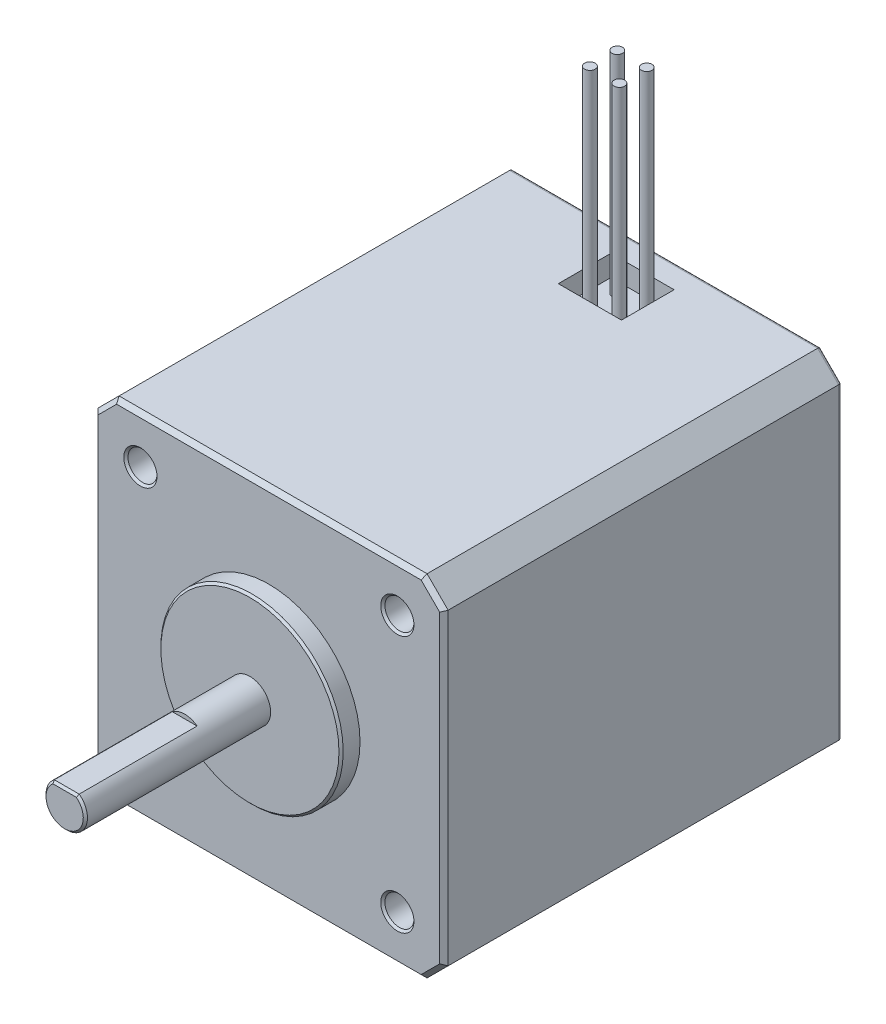
SolidWorks part; units mm, degrees
ref_plane "Plan de face" through (0, 0, 0) normal (0, 0, 1) x (1, 0, 0)
ref_plane "Plan de dessus" through (0, 0, 0) normal (0, 1, 0) x (1, 0, 0)
ref_plane "Plan de droite" through (0, 0, 0) normal (1, 0, 0) x (0, 0, -1)
ref_plane "Plan1" through (21.1211, 0, 0) normal (1, 0, 0) x (0, 0, -1)
sketch "Esquisse1" plane through (21.1211, 0, 0) normal (1, 0, 0) x (0, 0, -1)
  line L0 (0, 21.1211) -> (0, -21.1211)
  line L1 (0, -21.1211) -> (48.006, -21.1211)
  line L2 (48.006, -21.1211) -> (48.006, 21.1211)
  line L3 (48.006, 21.1211) -> (0, 21.1211)
extrude "Boss.-Extru.1" add sketch "Esquisse1" against normal blind 42.2423
sketch "Esquisse2" plane through (0, 0, 0) normal (0, 0, 1) x (1, 0, 0)
  circle A0 centre (0, 0) radius 11
extrude "Boss.-Extru.2" add sketch "Esquisse2" along normal blind 2.286
sketch "Esquisse3" plane through (0, 0, 2.286) normal (0, 0, 1) x (1, 0, 0)
  circle A0 centre (0, 0) radius 2.5
extrude "Boss.-Extru.3" add sketch "Esquisse3" along normal blind 22.352
sketch "Esquisse4" plane through (0, 0, 24.638) normal (0, 0, 1) x (1, 0, 0)
  line L0 (-1.5, 2) -> (1.5, 2)
  arc A0 (1.5, 2) -> (-1.5, 2) centre (0, 0) ccw
extrude "Enlèv. mat.-Extru.1" cut sketch "Esquisse4" against normal blind 14.478
sketch "Esquisse5" plane through (0, 21.1211, 0) normal (0, 1, 0) x (-1, 0, 0)
  line L0 (-3.81, -38.735) -> (-3.81, -45.085)
  line L1 (-3.81, -45.085) -> (3.81, -45.085)
  line L2 (3.81, -45.085) -> (3.81, -38.735)
  line L3 (3.81, -38.735) -> (-3.81, -38.735)
extrude "Enlèv. mat.-Extru.2" cut sketch "Esquisse5" against normal blind 2.54
ref_plane "Plan2" through (0, 0, -43.815) normal (0, 0, -1) x (-1, 0, 0)
sketch "Esquisse6" plane through (0, 0, -43.815) normal (0, 0, -1) x (-1, 0, 0)
  line L0 (-2.413, 18.5811) -> (-1.778, 18.5811)
  line L1 (-1.778, 18.5811) -> (-1.778, 43.9811)
  line L2 (-1.778, 43.9811) -> (-2.413, 43.9811)
  line L3 (-2.413, 43.9811) -> (-2.413, 18.5811)
  line L4 (-1.778, 18.5811) -> (-1.778, 43.9811) construction
revolve "Révolution1" add sketch "Esquisse6" angle 360 about L4
ref_plane "Plan3" through (0, 0, -40.513) normal (0, 0, -1) x (-1, 0, 0)
sketch "Esquisse7" plane through (0, 0, -40.513) normal (0, 0, -1) x (-1, 0, 0)
  line L0 (-2.413, 18.5811) -> (-1.778, 18.5811)
  line L1 (-1.778, 18.5811) -> (-1.778, 43.9811)
  line L2 (-1.778, 43.9811) -> (-2.413, 43.9811)
  line L3 (-2.413, 43.9811) -> (-2.413, 18.5811)
  line L4 (-1.778, 18.5811) -> (-1.778, 43.9811) construction
revolve "Révolution2" add sketch "Esquisse7" angle 360 about L4
sketch "Esquisse8" plane through (0, 0, -43.815) normal (0, 0, -1) x (-1, 0, 0)
  line L0 (1.143, 18.5811) -> (1.778, 18.5811)
  line L1 (1.778, 18.5811) -> (1.778, 43.9811)
  line L2 (1.778, 43.9811) -> (1.143, 43.9811)
  line L3 (1.143, 43.9811) -> (1.143, 18.5811)
  line L4 (1.778, 18.5811) -> (1.778, 43.9811) construction
revolve "Révolution3" add sketch "Esquisse8" angle 360 about L4
sketch "Esquisse9" plane through (0, 0, -40.513) normal (0, 0, -1) x (-1, 0, 0)
  line L0 (1.143, 18.5811) -> (1.778, 18.5811)
  line L1 (1.778, 18.5811) -> (1.778, 43.9811)
  line L2 (1.778, 43.9811) -> (1.143, 43.9811)
  line L3 (1.143, 43.9811) -> (1.143, 18.5811)
  line L4 (1.778, 18.5811) -> (1.778, 43.9811) construction
revolve "Révolution4" add sketch "Esquisse9" angle 360 about L4
hole_wizard "Dégagement M81" positions "Esquisse11" profile "Esquisse10" hole size "M8" standard "Ansi Metric"
sketch "Esquisse11" plane through (0, 0, -48.006) normal (0, 0, -1) x (-1, 0, 0)
  point P0 (0, 0)
sketch "Esquisse10" plane through (0, 0, -48.006) normal (1, 0, 0) x (0, 1, 0)
  line L0 (0, 0) -> (0, 4.191)
  line L1 (0, 4.191) -> (4.5085, 4.191)
  line L2 (4.5085, 4.191) -> (4.5085, 0)
  line L5 (4.5085, 0) -> (0, 0)
  line L10 (0, 4.191) -> (-4.5085, 4.191) construction
  line L11 (0, -6.35) -> (0, 107.95) construction
  dimension "Diamètre du perçage" = 9.017
  dimension "Profondeur du perçage" = 4.191
  dimension "Angle de pointe" = 180
hole_wizard "Diamètre du perçage Ø4.0 (4)1" positions "Esquisse13" profile "Esquisse12" hole size "Ø4.0" standard "Ansi Metric"
sketch "Esquisse13" plane through (0, 0, -48.006) normal (0, 0, -1) x (-1, 0, 0)
  point P0 (15.5, 15.5)
  point P1 (-15.5, -15.5)
  point P2 (15.5, -15.5)
  point P3 (-15.5, 15.5)
sketch "Esquisse12" plane through (-15.5, 15.5, -48.006) normal (1, 0, 0) x (0, 1, 0)
  line L0 (0, 0) -> (0, 4.191)
  line L1 (0, 4.191) -> (2, 4.191)
  line L2 (2, 4.191) -> (2, 0)
  line L5 (2, 0) -> (0, 0)
  line L10 (0, 4.191) -> (-2, 4.191) construction
  line L11 (0, -6.35) -> (0, 107.95) construction
  dimension "Diamètre du perçage" = 4
  dimension "Profondeur du perçage" = 4.191
  dimension "Angle de pointe" = 180
hole_wizard "Diamètre du perçage Ø3.5 (3.5)1" positions "Esquisse15" profile "Esquisse14" hole size "Ø3.5" standard "Ansi Metric"
sketch "Esquisse15" plane through (0, 0, 0) normal (0, 0, 1) x (1, 0, 0)
  point P0 (-15.5, 15.5)
  point P1 (15.5, 15.5)
  point P2 (-15.5, -15.5)
  point P3 (15.5, -15.5)
sketch "Esquisse14" plane through (-15.5, 15.5, 0) normal (1, 0, 0) x (0, -1, 0)
  line L0 (0, 0) -> (0, 4.572)
  line L1 (0, 4.572) -> (1.75, 4.572)
  line L2 (1.75, 4.572) -> (1.75, 0)
  line L5 (1.75, 0) -> (0, 0)
  line L10 (0, 4.572) -> (-1.75, 4.572) construction
  line L11 (0, -6.35) -> (0, 107.95) construction
  dimension "Diamètre du perçage" = 3.5
  dimension "Profondeur du perçage" = 4.572
  dimension "Angle de pointe" = 180
chamfer "Chanfrein1" distance 0.254 angle 45 12 edges at (-13.75, 15.5, 0) (17.25, 15.5, 0) (-13.75, -15.5, 0) (17.25, -15.5, 0) (0, 2, 24.638) (0, -2.5, 24.638) (11, 0, 2.286) (13.5, -15.5, -48.006) (-17.5, -15.5, -48.006) (13.5, 15.5, -48.006) (-17.5, 15.5, -48.006) (-4.5085, 0, -48.006)
chamfer "Chanfrein2" distance 2.54 angle 45 4 edges at (-21.1211, 21.1211, -24.003) (-21.1211, -21.1211, -24.003) (21.1211, 21.1211, -24.003) (21.1211, -21.1211, -24.003)
chamfer "Chanfrein3" distance 0.508 angle 45 8 edges at (19.8511, 19.8511, 0) (21.1211, 0, 0) (0, 21.1211, 0) (19.8511, -19.8511, 0) (-19.8511, 19.8511, 0) (0, -21.1211, 0) (-21.1211, 0, 0) (-19.8511, -19.8511, 0)
fillet "Congé1" radius 0.381 8 edges at (-21.1211, 0, -48.006) (-19.8511, 19.8511, -48.006) (-19.8511, -19.8511, -48.006) (0, 21.1211, -48.006) (0, -21.1211, -48.006) (19.8511, 19.8511, -48.006) (19.8511, -19.8511, -48.006) (21.1211, 0, -48.006)
